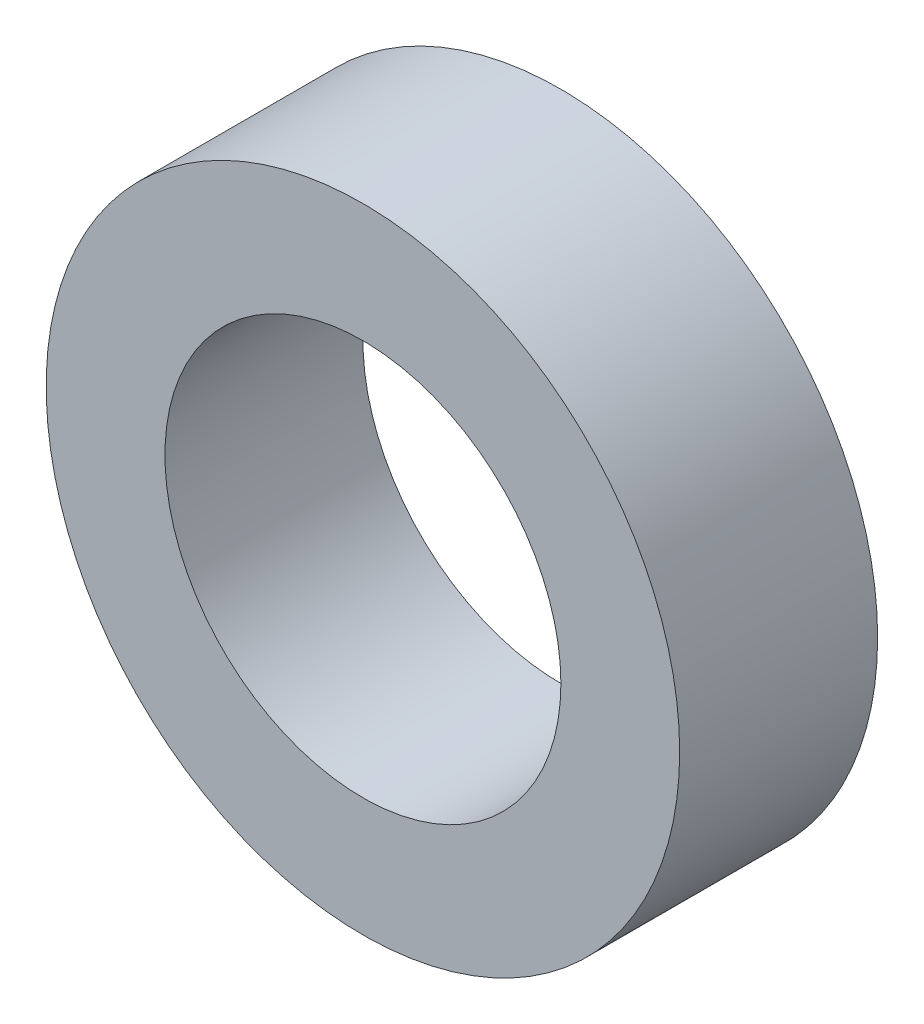
SolidWorks part; units mm, degrees
ref_plane "Plan de face" through (0, 0, 0) normal (0, 0, 1) x (1, 0, 0)
ref_plane "Plan de dessus" through (0, 0, 0) normal (0, 1, 0) x (1, 0, 0)
ref_plane "Plan de droite" through (0, 0, 0) normal (1, 0, 0) x (0, 0, -1)
sketch "Esquisse1" plane through (0, 0, 0) normal (0, 0, 1) x (1, 0, 0)
  circle A0 centre (0, 0) radius 2.5
  circle A1 centre (0, 0) radius 4
  dimension "D1" = 5
  dimension "D2" = 8
extrude "Boss.-Extru.1" add sketch "Esquisse1" against normal blind 2.5
